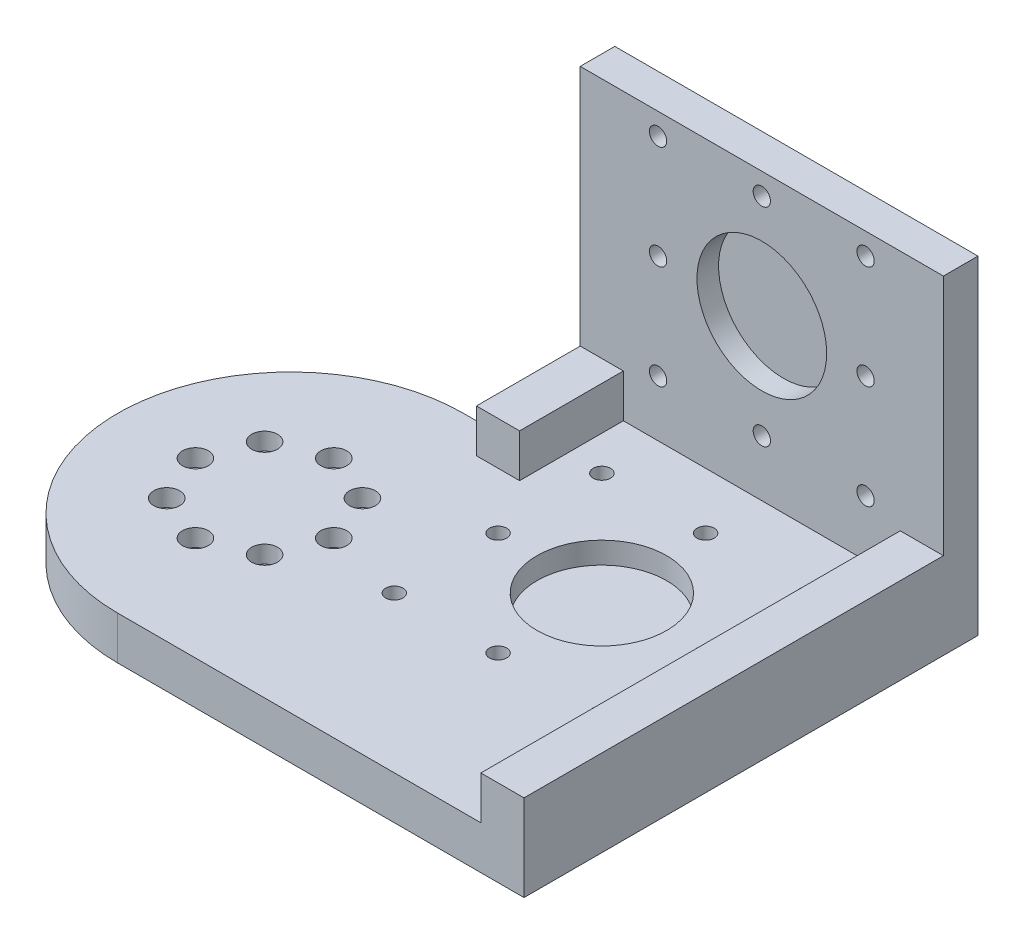
SolidWorks part; units mm, degrees
ref_plane "Front Plane" through (0, 0, 0) normal (0, 0, 1) x (1, 0, 0)
ref_plane "Top Plane" through (0, 0, 0) normal (0, 1, 0) x (1, 0, 0)
ref_plane "Right Plane" through (0, 0, 0) normal (1, 0, 0) x (0, 0, -1)
sketch "Sketch1" plane through (0, 0, 0) normal (0, 0, 1) x (1, 0, 0)
  line L0 (0, 0) -> (0, 24) construction
  line L1 (-29, -29) -> (29, -29)
  line L2 (-29, -29) -> (-29, 29)
  line L3 (-29, 29) -> (29, 29)
  line L4 (29, -29) -> (29, 29)
  line L5 (-29, -29) -> (29, 29) construction
  line L6 (-29, 29) -> (29, -29) construction
  line L7 (-29, 0) -> (29, 0) construction
  circle A1 centre (0, 24) radius 2
  circle A7 centre (-24, 24) radius 2
  circle A8 centre (24, 0) radius 2
  circle A9 centre (0, -24) radius 2
  circle A10 centre (-24, 0) radius 2
  circle A11 centre (24, -24) radius 2
  circle A12 centre (24, 24) radius 2
  circle A13 centre (-24, -24) radius 2
  point P0 (0, 0)
  point P21 (0, 0)
  point P22 (-3.4641, 2)
  dimension "D4" = 4
  dimension "D5" = 4
  dimension "D6" = 4
  dimension "D1" = 58
  dimension "D3" = 24
extrude "Boss-Extrude1" add sketch "Sketch1" along normal blind 8
sketch "Sketch13" plane through (0, 0, 8) normal (0, 0, 1) x (1, 0, 0)
  circle A0 centre (0, 0) radius 15
  point P0 (0, 0)
  dimension "D1" = 30
extrude "Cut-Extrude5" cut sketch "Sketch13" against normal blind 5
sketch "Sketch15" plane through (0, 0, 0) normal (0, 0, 1) x (1, 0, 0)
  line L1 (-29, -29) -> (29, -29)
  line L2 (-42, -29) -> (-42, 29)
  line L3 (-42, 29) -> (42, 29)
  line L4 (42, -29) -> (42, 29)
  line L5 (-42, -29) -> (42, 29) construction
  line L6 (-42, 29) -> (42, -29) construction
  line L7 (-29, -29) -> (29, -29)
  line L8 (-29, -29) -> (-29, 29)
  line L9 (-29, 29) -> (29, 29)
  line L10 (29, -29) -> (29, 29)
  line L11 (-29, -29) -> (29, 29) construction
  line L12 (-29, 29) -> (29, -29) construction
  line L13 (-29, -29) -> (29, -29)
  line L14 (-42, -29) -> (-42, -47)
  line L15 (-42, -47) -> (42, -47)
  line L16 (42, -29) -> (42, -47)
  point P0 (0, 0)
  point P5 (0, 0)
  dimension "D1" = 58
  dimension "D2" = 84
  dimension "D3" = 18
extrude "Boss-Extrude7" add sketch "Sketch15" along normal blind 8 contours L16 L4 L3 L10 L1 L8 L2 L14 L15
sketch "Sketch21" plane through (0, 0, 8) normal (0, 0, 1) x (1, 0, 0)
  line L1 (-42, -47) -> (42, -47)
  line L2 (-42, -47) -> (-42, -37)
  line L3 (-42, -37) -> (42, -37)
  line L4 (42, -47) -> (42, -37)
  dimension "D1" = 10
  dimension "D2" = 84
extrude "Boss-Extrude8" add sketch "Sketch21" along normal blind 114
sketch "Sketch22" plane through (0, 0, 8) normal (0, 0, 1) x (1, 0, 0)
  line L0 (0, -37) -> (0, -24) construction
  line L5 (42, -37) -> (-42, -37) construction
  line L6 (42, -27.02) -> (32.02, -27.02)
  line L7 (32.02, -37) -> (32.02, -27.02)
  line L8 (42, -37) -> (32.02, -37)
  line L9 (42, -37) -> (42, -27.02)
extrude "Boss-Extrude9" add sketch "Sketch22" along normal blind 114
sketch "Sketch23" plane through (0, -37, 0) normal (0, 1, 0) x (1, 0, 0)
  line L0 (-52, -105) -> (-32.937, -105)
  line L1 (-42, -65) -> (-52, -65) construction
  line L2 (-42, -122) -> (-42, -8) construction
  line L3 (-52, -25) -> (-32.937, -25)
  line L4 (-32.937, -25) -> (-32.937, -105)
  arc A1 (-52, -25) -> (-52, -105) centre (-52, -65) ccw
  dimension "D1" = 10
  dimension "D2" = 80
extrude "Boss-Extrude10" add sketch "Sketch23" against normal blind 10
sketch "Sketch27" plane through (0, 0, 0) normal (0, 1, 0) x (1, 0, 0)
  line L1 (-42, -122) -> (42, -122)
  line L2 (-42, -122) -> (-42, -105)
  line L3 (-42, -105) -> (42, -105)
  line L4 (42, -122) -> (42, -105)
  line L5 (42, -122) -> (42, -8) construction
  dimension "D1" = 17
  dimension "D2" = 84
extrude "Cut-Extrude9" cut sketch "Sketch27" against normal through all
sketch "Sketch28" plane through (0, -37, 0) normal (0, 1, 0) x (1, 0, 0)
  line L0 (-42, -25) -> (-42, -105) construction
  line L1 (-52, -105) -> (32.02, -105) construction
  line L2 (-42, -65) -> (-58, -65) construction
  circle A0 centre (-42, -65) radius 2
  circle A1 centre (-46.6863, -76.3137) radius 2
  circle A2 centre (-58, -81) radius 2
  circle A3 centre (-69.3137, -76.3137) radius 2
  circle A4 centre (-74, -65) radius 2
  circle A5 centre (-69.3137, -53.6863) radius 2
  circle A6 centre (-58, -49) radius 2
  circle A7 centre (-46.6863, -53.6863) radius 2
  point P24 (-58, -65)
  dimension "D2" = 4
  dimension "D1" = 16
  dimension "D3" = 8
extrude "Cut-Extrude10" cut sketch "Sketch28" against normal through all
sketch "Sketch29" plane through (0, -37, 0) normal (0, 1, 0) x (1, 0, 0)
  line L0 (-58, -49) -> (-58, -65) construction
  circle A0 centre (-58, -49) radius 3
  circle A1 centre (-46.6863, -53.6863) radius 3
  circle A2 centre (-42, -65) radius 3
  circle A3 centre (-46.6863, -76.3137) radius 3
  circle A4 centre (-58, -81) radius 3
  circle A5 centre (-69.3137, -76.3137) radius 3
  circle A6 centre (-74, -65) radius 3
  circle A7 centre (-69.3137, -53.6863) radius 3
  point P20 (-58, -65)
  dimension "D1" = 6
  dimension "D3" = 8
  dimension "D2" = 16
extrude "Cut-Extrude11" cut sketch "Sketch29" against normal blind 4
sketch "Sketch31" plane through (0, 0, 8) normal (0, 0, 1) x (1, 0, 0)
  line L1 (-42, -37) -> (-32.02, -37)
  line L2 (-42, -37) -> (-42, -27.02)
  line L3 (-42, -27.02) -> (-32.02, -27.02)
  line L4 (-32.02, -37) -> (-32.02, -27.02)
  dimension "D1" = 9.98
extrude "Boss-Extrude11" add sketch "Sketch31" along normal blind 24
sketch "Sketch36" plane through (0, -37, 0) normal (0, 1, 0) x (1, 0, 0)
  line L0 (0, -8) -> (0, -21) construction
  line L1 (32.02, -8) -> (-32.02, -8) construction
  line L2 (0, -21) -> (0, -45) construction
  line L3 (0, -21) -> (-24, -21) construction
  line L4 (24, -45) -> (-24, -45) construction
  circle A0 centre (0, -21) radius 2
  circle A1 centre (24, -45) radius 2
  circle A2 centre (0, -69) radius 2
  circle A3 centre (-24, -45) radius 2
  circle A4 centre (-24, -21) radius 2
  circle A5 centre (24, -21) radius 2
  circle A6 centre (24, -69) radius 2
  circle A7 centre (-24, -69) radius 2
  circle A8 centre (0, -45) radius 15
  point P16 (0, -45)
  dimension "D3" = 4
  dimension "D5" = 4
  dimension "D6" = 30
  dimension "D1" = 13
  dimension "D2" = 24
  dimension "D4" = 4
extrude "Cut-Extrude12" cut sketch "Sketch36" against normal blind 20
sketch "Sketch37" plane through (0, -47, 0) normal (0, -1, 0) x (1, 0, 0)
  circle A0 centre (0, 45) radius 15
extrude "Boss-Extrude12" add sketch "Sketch37" against normal blind 5 separate body
equation "\"ๅจภ\"=94"
